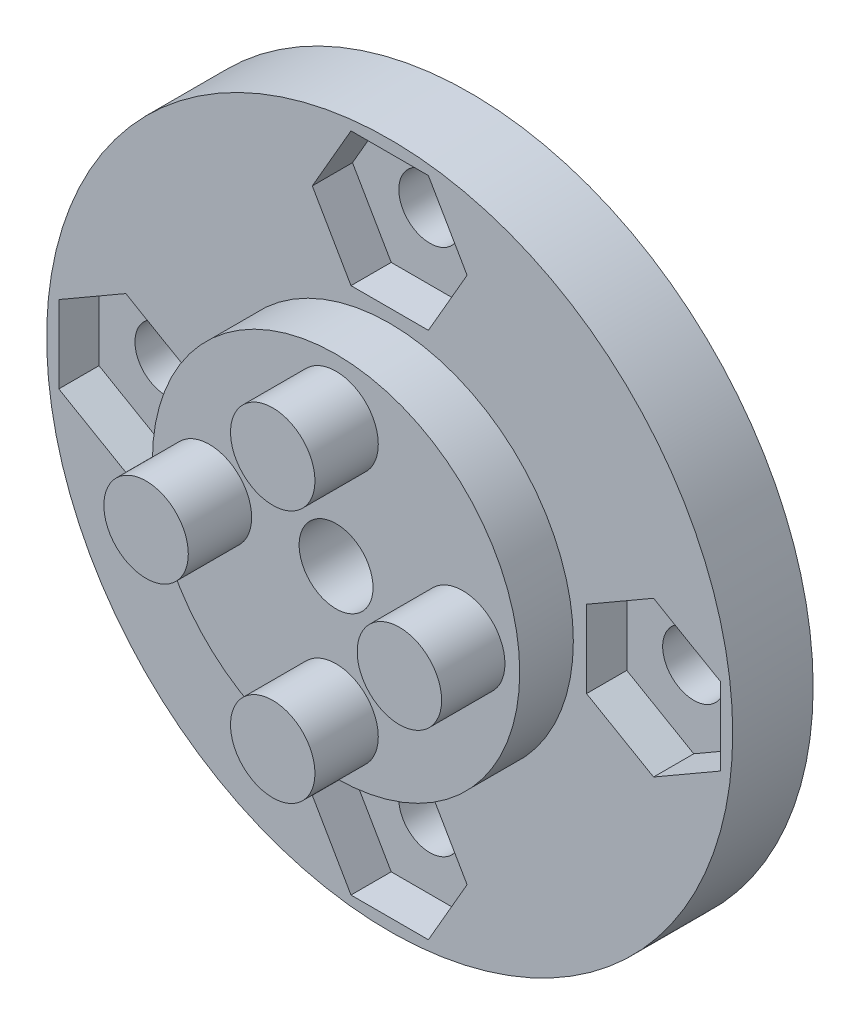
SolidWorks part; units mm, degrees
ref_plane "Front Plane" through (0, 0, 0) normal (0, 0, 1) x (1, 0, 0)
ref_plane "Top Plane" through (0, 0, 0) normal (0, 1, 0) x (1, 0, 0)
ref_plane "Right Plane" through (0, 0, 0) normal (1, 0, 0) x (0, 0, -1)
sketch "Sketch1" plane through (0, 0, 0) normal (0, 0, 1) x (1, 0, 0)
  circle A0 centre (0, 0) radius 8.7
  dimension "D1" = 17.4
extrude "Boss-Extrude1" add sketch "Sketch1" along normal blind 2.54
sketch "Sketch2" plane through (0, 0, 2.54) normal (0, 0, 1) x (1, 0, 0)
  line L0 (0, 6) -> (0, 0) construction
  line L1 (0, 0) -> (0, -6) construction
  line L3 (6, 0) -> (0, 0) construction
  line L4 (-6, 0) -> (0, 0) construction
  circle A0 centre (0, 6) radius 2
  circle A1 centre (6, 0) radius 2
  circle A2 centre (0, -6) radius 2
  circle A3 centre (-6, 0) radius 2
  dimension "D2" = 4
  dimension "D1" = 6
extrude "Boss-Extrude2" add sketch "Sketch2" along normal blind 3
sketch "Sketch3" plane through (0, 0, 0) normal (0, 0, -1) x (-1, 0, 0)
  circle A0 centre (0, 0) radius 16.25
  dimension "D1" = 32.5
extrude "Boss-Extrude3" add sketch "Sketch3" along normal blind 3.81
sketch "Sketch4" plane through (0, 0, 0) normal (0, 0, 1) x (1, 0, 0)
  line L0 (0, 0) -> (-12.5, 0) construction
  line L2 (-12.5, 3.6662) -> (-15.675, 1.8331)
  line L3 (-15.675, 1.8331) -> (-15.675, -1.8331)
  line L4 (-15.675, -1.8331) -> (-12.5, -3.6662)
  line L5 (-12.5, -3.6662) -> (-9.325, -1.8331)
  line L6 (-9.325, -1.8331) -> (-9.325, 1.8331)
  line L7 (-9.325, 1.8331) -> (-12.5, 3.6662)
  circle A0 centre (-12.5, 0) radius 3.175 construction
  dimension "D1" = 6.35
  dimension "D2" = 12.5
extrude "Cut-Extrude1" cut sketch "Sketch4" against normal blind 1.905
hole_wizard "#4 Clearance Hole1" positions "Sketch5" profile "Sketch6" hole size "#4" standard "ANSI Inch" end condition through all
sketch "Sketch5" plane through (0, 0, -1.905) normal (0, 0, 1) x (1, 0, 0)
  point P0 (-12.5, 0)
sketch "Sketch6" plane through (-12.5, 0, -1.905) normal (1, 0, 0) x (0, -1, 0)
  line L0 (0, 0) -> (0, 1.905)
  line L1 (0, 1.905) -> (1.4732, 1.905)
  line L2 (1.4732, 1.905) -> (1.4732, 0)
  line L5 (1.4732, 0) -> (0, 0)
  line L11 (0, -6.35) -> (0, 107.95) construction
  dimension "Thru Hole Dia." = 2.9464
  dimension "Thru Hole Depth" = 1.905
pattern_circular "CirPattern1" count 4 over 360 about axis through (0, 0, 0) along (0, 0, 1) of "Cut-Extrude1", "#4 Clearance Hole1"
sketch "Sketch8" plane through (0, 0, 2.54) normal (0, 0, 1) x (1, 0, 0)
  circle A0 centre (0, 0) radius 1.75
  dimension "D1" = 3.5
extrude "Cut-Extrude2" cut sketch "Sketch8" against normal blind 2.5
sketch "Sketch9" plane through (0, 0, 0.04) normal (0, 0, 1) x (1, 0, 0)
  circle A0 centre (0, 0) radius 3.5
  dimension "D1" = 7
extrude "Cut-Extrude3" cut sketch "Sketch9" against normal through all
